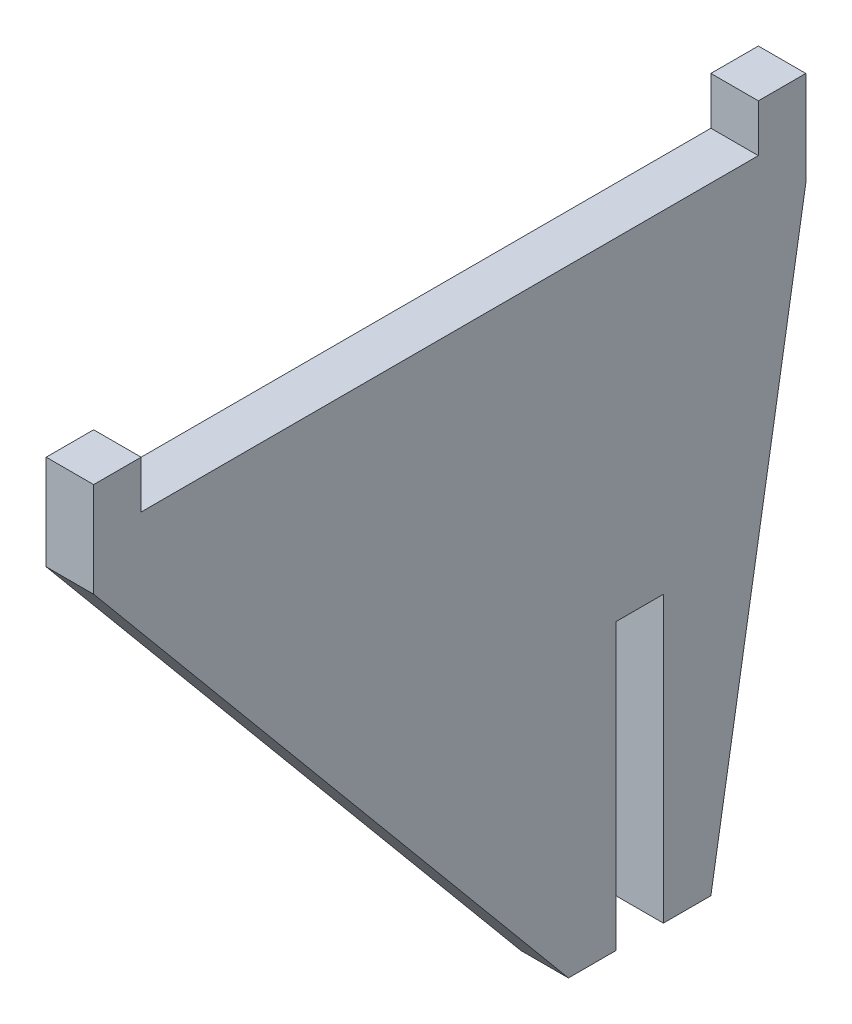
SolidWorks part; units mm, degrees
material "6061-T4 (SS)"
ref_plane "Front Plane" through (0, 0, 0) normal (0, 0, 1) x (1, 0, 0)
ref_plane "Top Plane" through (0, 0, 0) normal (0, 1, 0) x (1, 0, 0)
ref_plane "Right Plane" through (0, 0, 0) normal (1, 0, 0) x (0, 0, -1)
sketch "Sketch1" plane through (-161.1706, 0, 0) normal (1, 0, 0) x (0, 0, -1)
  line L0 (-799.6114, 609.6) -> (-786.9114, 609.6)
  line L1 (-786.9114, 609.6) -> (-786.9114, 596.9)
  line L2 (-786.9114, 596.9) -> (-621.8114, 596.9)
  line L3 (-799.6114, 609.6) -> (-799.6114, 596.9)
  line L4 (-799.6114, 596.9) -> (-799.6114, 584.2)
  line L5 (-621.8114, 596.9) -> (-621.8114, 609.6)
  line L6 (-621.8114, 609.6) -> (-609.1114, 609.6)
  line L7 (-609.1114, 609.6) -> (-609.1114, 596.9)
  line L8 (-609.1114, 596.9) -> (-609.1114, 584.2)
  line L9 (-609.1114, 584.2) -> (-634.5114, 431.8)
  line L10 (-634.5114, 431.8) -> (-647.2114, 431.8)
  line L12 (-647.2114, 431.8) -> (-647.2114, 508)
  line L13 (-647.2114, 457.2) -> (-647.2114, 609.6) construction
  line L14 (-647.2114, 508) -> (-659.9114, 508)
  line L16 (-659.9114, 508) -> (-659.9114, 431.8)
  line L18 (-659.9114, 431.8) -> (-672.6114, 431.8)
  line L19 (-672.6114, 431.8) -> (-799.6114, 584.2)
  line L20 (-799.6114, 508) -> (-659.9114, 508) construction
  line L22 (-799.6114, 584.2) -> (-659.9114, 584.2) construction
  line L23 (-799.6114, 431.8) -> (-659.9114, 431.8) construction
  line L24 (-647.2114, 533.4) -> (-647.2114, 381) construction
  line L25 (-786.9114, 596.9) -> (-786.9114, 609.6) construction
  line L26 (-621.8114, 596.9) -> (-621.8114, 609.6) construction
  line L27 (-799.6114, 596.9) -> (-539.3835, 596.9) construction
  line L28 (-659.9114, 0) -> (-659.9114, 609.6) construction
  line L29 (-799.6114, 584.2) -> (-659.9114, 584.2) construction
  line L30 (-659.9114, 596.9) -> (-659.9114, 508) construction
  dimension "D1" = 76.2
  dimension "D2" = 76.2
extrude "Boss-Extrude1" add sketch "Sketch1" along normal up to vertex (12.7 mm away)
